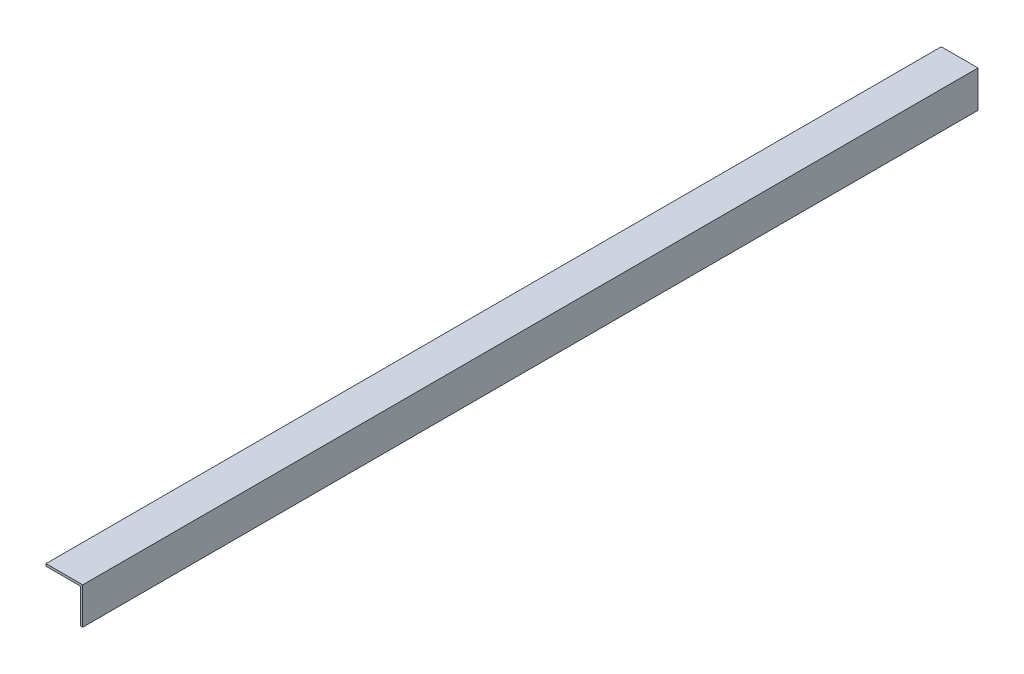
SolidWorks part; units mm, degrees
ref_plane "Front Plane" through (0, 0, 0) normal (0, 0, 1) x (1, 0, 0)
ref_plane "Top Plane" through (0, 0, 0) normal (0, 1, 0) x (1, 0, 0)
ref_plane "Right Plane" through (0, 0, 0) normal (1, 0, 0) x (0, 0, -1)
other "Configuration Table"
sketch "Sketch1" plane through (0, 0, 0) normal (0, 0, 1) x (1, 0, 0)
  line L0 (662, 1042) -> (660, 1042)
  line L1 (660, 1042) -> (660, 1072)
  line L2 (660, 1072) -> (630, 1072)
  line L3 (630, 1072) -> (630, 1074)
  line L4 (630, 1074) -> (662, 1074)
  line L5 (662, 1074) -> (662, 1042)
extrude "PRESS_tepsi_rafi_kosebent_sag_1" add sketch "Sketch1" against normal blind 780 from offset 20 separate body
